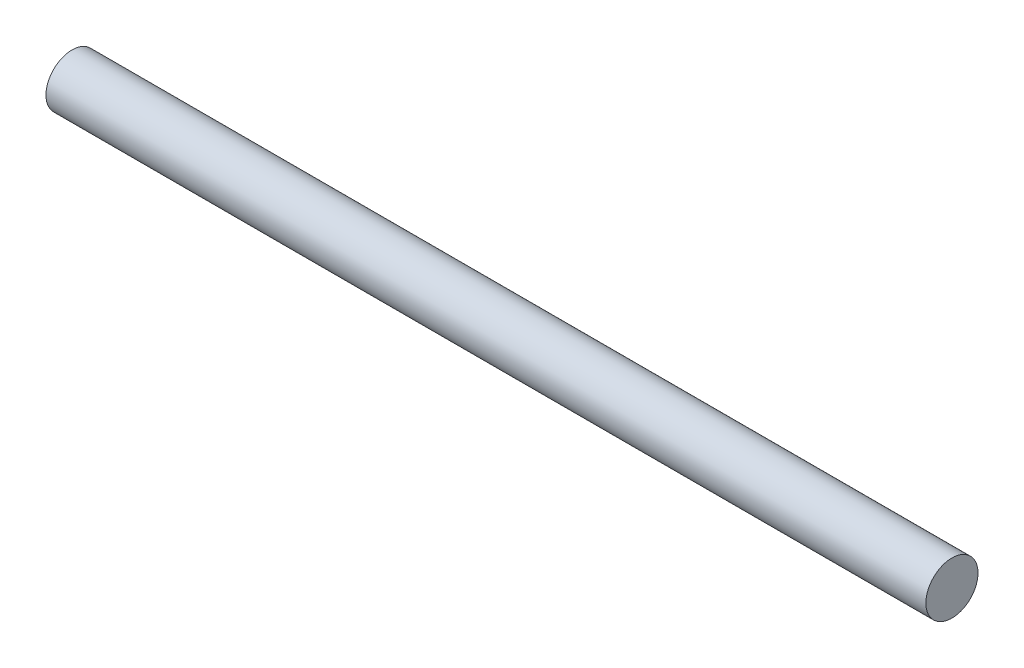
SolidWorks part; units mm, degrees
ref_plane "Front Plane" through (0, 0, 0) normal (0, 0, 1) x (1, 0, 0)
ref_plane "Top Plane" through (0, 0, 0) normal (0, 1, 0) x (1, 0, 0)
ref_plane "Right Plane" through (0, 0, 0) normal (1, 0, 0) x (0, 0, -1)
sketch "Sketch1" plane through (0, 0, 0) normal (1, 0, 0) x (0, 0, -1)
  circle A0 centre (0, 0) radius 4
  dimension "D1" = 8
extrude "Boss-Extrude1" add sketch "Sketch1" along normal blind 120
sketch "Sketch2" plane through (120, 0, 0) normal (1, 0, 0) x (0, 0, -1)
  circle A0 centre (0, 0) radius 4
extrude "Boss-Extrude2" add sketch "Sketch2" along normal blind 15
